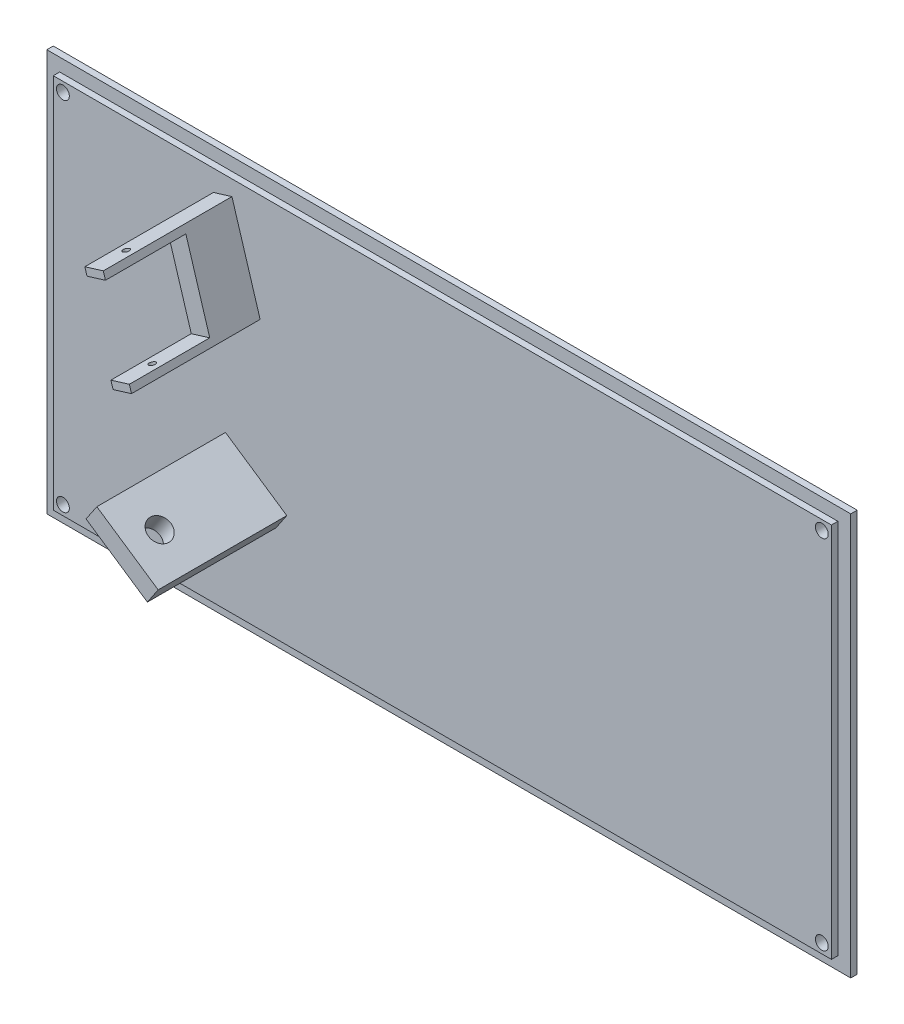
SolidWorks part; units mm, degrees
ref_plane "Ebene vorne" through (0, 0, 0) normal (0, 0, 1) x (1, 0, 0)
ref_plane "Ebene oben" through (0, 0, 0) normal (0, 1, 0) x (1, 0, 0)
ref_plane "Ebene rechts" through (0, 0, 0) normal (1, 0, 0) x (0, 0, -1)
sketch "Skizze1" plane through (0, 0, 0) normal (0, 0, 1) x (1, 0, 0)
  line L1 (0, 125) -> (250, 125)
  line L2 (0, 125) -> (0, 0)
  line L3 (0, 0) -> (250, 0)
  line L4 (250, 125) -> (250, 0)
  dimension "D1" = 250
  dimension "D2" = 125
extrude "Aufsatz-Linear austragen1" add sketch "Skizze1" along normal blind 2 contours L2 L1 L4 L3
sketch "Skizze2" plane through (0, 0, 2) normal (0, 0, 1) x (1, 0, 0)
  line L0 (0, 125) -> (0, 0) construction
  line L1 (4, 121) -> (246, 121)
  line L2 (4, 121) -> (4, 4)
  line L3 (4, 4) -> (246, 4)
  line L4 (246, 121) -> (246, 4)
  line L5 (0, 125) -> (250, 125) construction
  line L6 (0, 0) -> (250, 0) construction
  line L7 (250, 125) -> (250, 0) construction
  dimension "D1" = 4
  dimension "D2" = 4
  dimension "D3" = 4
  dimension "D4" = 4
extrude "Aufsatz-Linear austragen2" add sketch "Skizze2" along normal blind 2
sketch "Skizze3" plane through (0, 0, 4) normal (0, 0, 1) x (1, 0, 0)
  line L0 (246, 121) -> (4, 121) construction
  line L1 (4, 121) -> (4, 4) construction
  line L2 (4, 121) -> (4, 4) construction
  line L3 (4, 4) -> (246, 4) construction
  line L4 (246, 4) -> (246, 121) construction
  line L5 (246, 121) -> (4, 121) construction
  circle A0 centre (7, 118) radius 2
  circle A1 centre (7, 7) radius 2
  circle A2 centre (243, 7) radius 2
  circle A3 centre (243, 118) radius 2
  dimension "D1" = 3
  dimension "D3" = 3
  dimension "D5" = 3
  dimension "D2" = 3
  dimension "D4" = 3
  dimension "D6" = 3
  dimension "D7" = 3
  dimension "D8" = 3
extrude "Schnitt-Linear austragen1" cut sketch "Skizze3" against normal blind 32
sketch "Skizze4" plane through (0, 0, 4) normal (0, 0, 1) x (1, 0, 0)
  line L0 (246, 121) -> (246, 4) construction
  line L1 (4, 62.5) -> (246, 62.5) construction
  line L3 (4, 121) -> (4, 4) construction
  line L4 (4, 62.5) -> (90.7298, 121) construction
  line L5 (3.8274, 56.5) -> (246, 56.5) construction
  line L6 (246, 121) -> (4, 121) construction
  line L15 (4, 62.5) -> (90.7298, 4) construction
  line L16 (4, 4) -> (246, 4) construction
  line L17 (3.8274, 56.5) -> (3.8274, 68.5) construction
  line L18 (4, 62.5) -> (195.3449, 121) construction
  line L26 (3.8274, 68.5) -> (246, 68.5) construction
  line L31 (62.5953, 85.7783) -> (68.3331, 87.5325)
  line L32 (62.5953, 85.7783) -> (53.8241, 114.4675)
  line L33 (68.3331, 87.5325) -> (59.5619, 116.2217)
  line L34 (53.8241, 114.4675) -> (59.5619, 116.2217)
  line L35 (53.8241, 114.4675) -> (68.3331, 87.5325) construction
  line L37 (37.4248, 21.8614) -> (54.2006, 46.7326) construction
  line L38 (54.2006, 46.7326) -> (73.2684, 33.8711) construction
  line L39 (37.4248, 21.8614) -> (56.4926, 9) construction
  line L40 (56.4926, 9) -> (73.2684, 33.8711) construction
  line L41 (54.2006, 46.7326) -> (73.2684, 33.8711)
  line L42 (54.2006, 46.7326) -> (57.5557, 51.7068)
  line L43 (73.2684, 33.8711) -> (76.6236, 38.8454)
  line L44 (57.5557, 51.7068) -> (76.6236, 38.8454)
  line L45 (0, 125) -> (250, 125) construction
  point P11 (3.8274, 62.5)
  point P14 (61.0786, 101)
  point P27 (45.8127, 34.297)
  point P36 (7.8918, 125)
  dimension "D1" = 34
  dimension "D2" = 34
  dimension "D3" = 12
  dimension "D4" = 17
  dimension "D5" = 6
  dimension "D6" = 30
  dimension "D7" = 24
  dimension "D8" = 30
  dimension "D9" = 23
  dimension "D10" = 6
  dimension "D11" = 5
extrude "Aufsatz-Linear austragen3" add sketch "Skizze4" along normal blind 40
sketch "Skizze7" plane through (0, 0, 44) normal (0, 0, 1) x (1, 0, 0)
  line L0 (54.4966, 112.268) -> (60.2344, 114.0222)
  line L1 (54.4966, 112.268) -> (61.9228, 87.9778)
  line L2 (60.2344, 114.0222) -> (67.6606, 89.732)
  line L3 (61.9228, 87.9778) -> (67.6606, 89.732)
  line L4 (53.8241, 114.4675) -> (62.5953, 85.7783) construction
  line L5 (68.3331, 87.5325) -> (59.5619, 116.2217) construction
  line L6 (57.3655, 113.1451) -> (56.693, 115.3446) construction
  line L7 (59.5619, 116.2217) -> (53.8241, 114.4675) construction
  line L8 (64.7917, 88.8549) -> (65.4642, 86.6554) construction
  line L9 (62.5953, 85.7783) -> (68.3331, 87.5325) construction
  dimension "D1" = 25.4
extrude "Schnitt-Linear austragen2" cut sketch "Skizze7" against normal blind 25
sketch "Skizze8" plane through (-27.4037, 89.6336, 0) normal (-0.2924, 0.9563, 0) x (0.9563, 0.2924, 0)
  line L0 (90.9393, -44) -> (90.9393, -4) construction
  line L1 (90.9393, -4) -> (84.9393, -4) construction
  circle A0 centre (87.9393, -34) radius 1
  dimension "D1" = 3
  dimension "D2" = 30
extrude "Schnitt-Linear austragen3" cut sketch "Skizze8" against normal blind 40
sketch "Skizze9" plane through (41.9683, 62.2206, 0) normal (0.5592, 0.829, 0) x (0.829, -0.5592, 0)
  line L0 (30.3018, -34) -> (18.8018, -34) construction
  line L1 (18.8018, -44) -> (18.8018, -4) construction
  line L2 (30.3018, -34) -> (41.8018, -34) construction
  line L3 (41.8018, -44) -> (41.8018, -4) construction
  line L4 (41.8018, -4) -> (18.8018, -4) construction
  circle A0 centre (30.3018, -34) radius 3.4931
  dimension "D1" = 30
extrude "Schnitt-Linear austragen4" cut sketch "Skizze9" against normal blind 20
